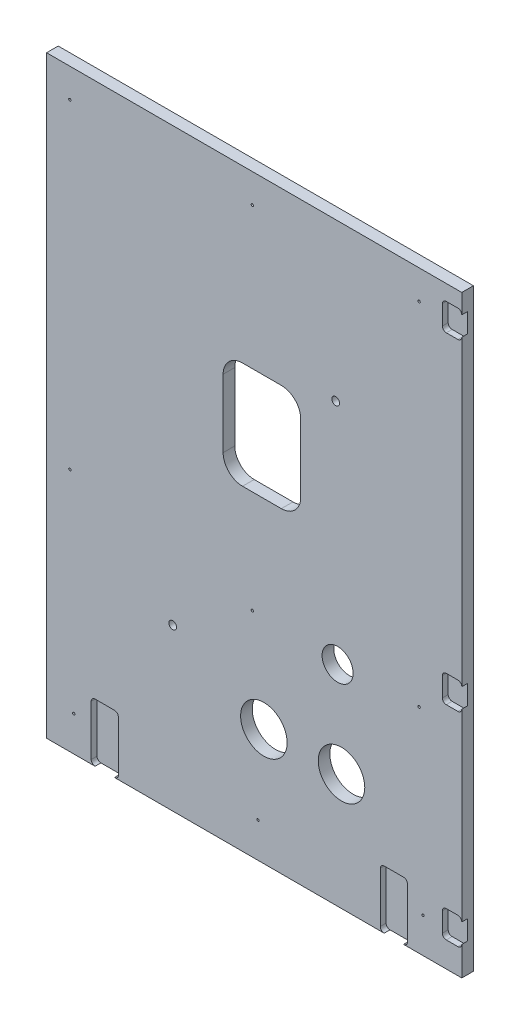
SolidWorks part; units mm, degrees
material "Фанера, берёза, ФСФ ВВ/С ГОСТ 3916.1-96"
ref_plane "Спереди" through (0, 0, 0) normal (0, 0, 1) x (1, 0, 0)
ref_plane "Сверху" through (0, 0, 0) normal (0, 1, 0) x (1, 0, 0)
ref_plane "Справа" through (0, 0, 0) normal (1, 0, 0) x (0, 0, -1)
sketch "Эскиз1" plane through (0, 0, 0) normal (0, 0, 1) x (1, 0, 0)
  line L1 (-535, -765) -> (535, -765)
  line L2 (-535, -765) -> (-535, 765)
  line L3 (-535, 765) -> (535, 765)
  line L4 (535, -765) -> (535, 765)
  line L5 (0, 765) -> (0, -765) construction
  line L6 (-535, 0) -> (535, 0) construction
  point P0 (0, 0)
  dimension "D1" = 1070
  dimension "D2" = 1530
extrude "Бобышка-Вытянуть1" add sketch "Эскиз1" along normal mid plane 30
sketch "Эскиз2" plane through (0, 0, 15) normal (0, 0, 1) x (1, 0, 0)
  line L0 (-535, 765) -> (-535, -765) construction
  line L1 (-30, 325) -> (70, 325)
  line L2 (-80, 275) -> (-80, 100)
  line L3 (-30, 50) -> (70, 50)
  line L4 (120, 275) -> (120, 100)
  line L5 (535, 765) -> (-535, 765) construction
  line L6 (535, -765) -> (535, 765) construction
  line L7 (-535, -765) -> (535, -765) construction
  arc A0 (70, 50) -> (120, 100) centre (70, 100) ccw
  arc A1 (-80, 100) -> (-30, 50) centre (-30, 100) ccw
  arc A2 (70, 325) -> (120, 275) centre (70, 275) cw
  arc A3 (-30, 325) -> (-80, 275) centre (-30, 275) ccw
  circle A4 centre (215, -225) radius 40
  circle A5 centre (225, -465) radius 60
  circle A6 centre (25, -465) radius 60
  circle A7 centre (210, 360) radius 10
  circle A8 centre (-210, -350) radius 10
  point P4 (20, 50)
  dimension "D5" = 50
  dimension "D6" = 80
  dimension "D9" = 120
  dimension "D13" = 20
  dimension "D1" = 275
  dimension "D2" = 200
  dimension "D3" = 455
  dimension "D4" = 440
  dimension "D7" = 320
  dimension "D8" = 540
  dimension "D10" = 310
  dimension "D11" = 300
  dimension "D12" = 510
  dimension "D14" = 405
  dimension "D15" = 325
  dimension "D16" = 325
  dimension "D17" = 415
extrude "Вырез-Вытянуть1" cut sketch "Эскиз2" against normal through all
sketch "Эскиз4" plane through (0, 0, 15) normal (0, 0, 1) x (1, 0, 0)
  line L0 (535, -765) -> (535, 765) construction
  line L1 (535, 765) -> (-535, 765) construction
  line L2 (-535, -765) -> (535, -765) construction
  line L3 (-535, 765) -> (-535, -765) construction
  point P0 (167.9177, -661.5146)
  line B0 (495, -105) -> (525, -105)
  line B1 (485, -115) -> (485, -165)
  line B2 (495, -175) -> (525, -175)
  line B3 (535, -115) -> (535, -165)
  arc B4 (525, -175) -> (535, -165) centre (525, -165) ccw
  arc B5 (485, -165) -> (495, -175) centre (495, -165) ccw
  arc B6 (525, -105) -> (535, -115) centre (525, -115) cw
  arc B7 (495, -105) -> (485, -115) centre (495, -115) ccw
  line B8 (495, -630) -> (525, -630)
  line B9 (485, -640) -> (485, -690)
  line B10 (495, -700) -> (525, -700)
  line B11 (535, -640) -> (535, -690)
  arc B12 (525, -700) -> (535, -690) centre (525, -690) ccw
  arc B13 (485, -690) -> (495, -700) centre (495, -690) ccw
  arc B14 (525, -630) -> (535, -640) centre (525, -640) cw
  arc B15 (495, -630) -> (485, -640) centre (495, -640) ccw
  line B16 (-385, -615) -> (-385, -765) construction
  line B17 (-410, -615) -> (-360, -615)
  line B18 (-420, -625) -> (-420, -755)
  line B19 (-410, -765) -> (-360, -765)
  line B20 (-350, -625) -> (-350, -755)
  arc B21 (-360, -765) -> (-350, -755) centre (-360, -755) ccw
  arc B22 (-420, -755) -> (-410, -765) centre (-410, -755) ccw
  arc B23 (-360, -615) -> (-350, -625) centre (-360, -625) cw
  arc B24 (-410, -615) -> (-420, -625) centre (-410, -625) ccw
  line B25 (495, 725) -> (525, 725)
  line B26 (485, 715) -> (485, 665)
  line B27 (495, 655) -> (525, 655)
  line B28 (535, 715) -> (535, 665)
  arc B29 (525, 655) -> (535, 665) centre (525, 665) ccw
  arc B30 (485, 665) -> (495, 655) centre (495, 665) ccw
  arc B31 (525, 725) -> (535, 715) centre (525, 715) cw
  arc B32 (495, 725) -> (485, 715) centre (495, 715) ccw
  line B33 (335, -615) -> (385, -615)
  line B34 (325, -625) -> (325, -755)
  line B35 (335, -765) -> (385, -765)
  line B36 (395, -625) -> (395, -755)
  arc B37 (385, -765) -> (395, -755) centre (385, -755) ccw
  arc B38 (325, -755) -> (335, -765) centre (335, -755) ccw
  arc B39 (385, -615) -> (395, -625) centre (385, -625) cw
  arc B40 (335, -615) -> (325, -625) centre (335, -625) ccw
  dimension "D1" = 40
  dimension "D2" = 870
  dimension "D3" = 65
  dimension "D4" = 115
  dimension "D5" = 140
sketch_block_instance "Блок1-2"
sketch_block "Блок1" parameters "D3"=10, "D1"=70, "D2"=50
sketch_block_instance "Блок1-3"
sketch_block "Блок1" parameters "D3"=10, "D1"=70, "D2"=50
sketch_block_instance "Блок3-1"
sketch_block "Блок3" parameters "D2"=10, "D1"=70, "D3"=50
sketch_block_instance "Блок1-1"
sketch_block "Блок1" parameters "D3"=10, "D1"=70, "D2"=50
sketch_block_instance "Блок3-2"
extrude "Вырез-Вытянуть2" cut sketch "Эскиз4" against normal blind 15
sketch "Эскиз5" plane through (0, 0, 15) normal (0, 0, 1) x (1, 0, 0)
  line L0 (535, 765) -> (-535, 765) construction
  line L1 (-535, 765) -> (-535, -765) construction
  line L2 (-535, -765) -> (-410, -765) construction
  line L3 (-360, -765) -> (335, -765) construction
  line L4 (385, -765) -> (535, -765) construction
  line L5 (535, -765) -> (535, -690) construction
  point P0 (-492.6091, 591.725)
  circle B0 centre (-475, 690) radius 3
  circle B1 centre (-5, 690) radius 3
  circle B2 centre (425, 690) radius 3
  circle B3 centre (-475, -135) radius 3
  circle B4 centre (-5, -215) radius 3
  circle B5 centre (425, -215) radius 3
  circle B6 centre (-465, -675) radius 3
  circle B7 centre (10, -675) radius 3
  circle B8 centre (435, -675) radius 3
  dimension "D1" = 75
  dimension "D2" = 60
  dimension "D3" = 470
  dimension "D4" = 430
  dimension "D5" = 825
  dimension "D6" = 905
  dimension "D7" = 70
  dimension "D8" = 90
  dimension "D9" = 90
  dimension "D10" = 545
  dimension "D11" = 90
  dimension "D12" = 100
sketch_block_instance "Блок4-1"
sketch_block "Блок4" parameters "D1"=6
sketch_block_instance "Блок4-2"
sketch_block_instance "Блок4-3"
sketch_block_instance "Блок4-4"
sketch_block_instance "Блок4-5"
sketch_block_instance "Блок4-6"
sketch_block_instance "Блок4-7"
sketch_block_instance "Блок4-8"
sketch_block_instance "Блок4-9"
extrude "Вырез-Вытянуть3" cut sketch "Эскиз5" against normal through all
equation "\"ширина 1-я панель\"=1145"
equation "\"длина панелей\"=1530"
equation "\"толщина дсп\"=30"
equation "\"ширина 2-я панель\"=1070"
equation "\"D2@Эскиз1\"=\"длина панелей\""
equation "\"D1@Эскиз1\"=\"ширина 2-я панель\""
